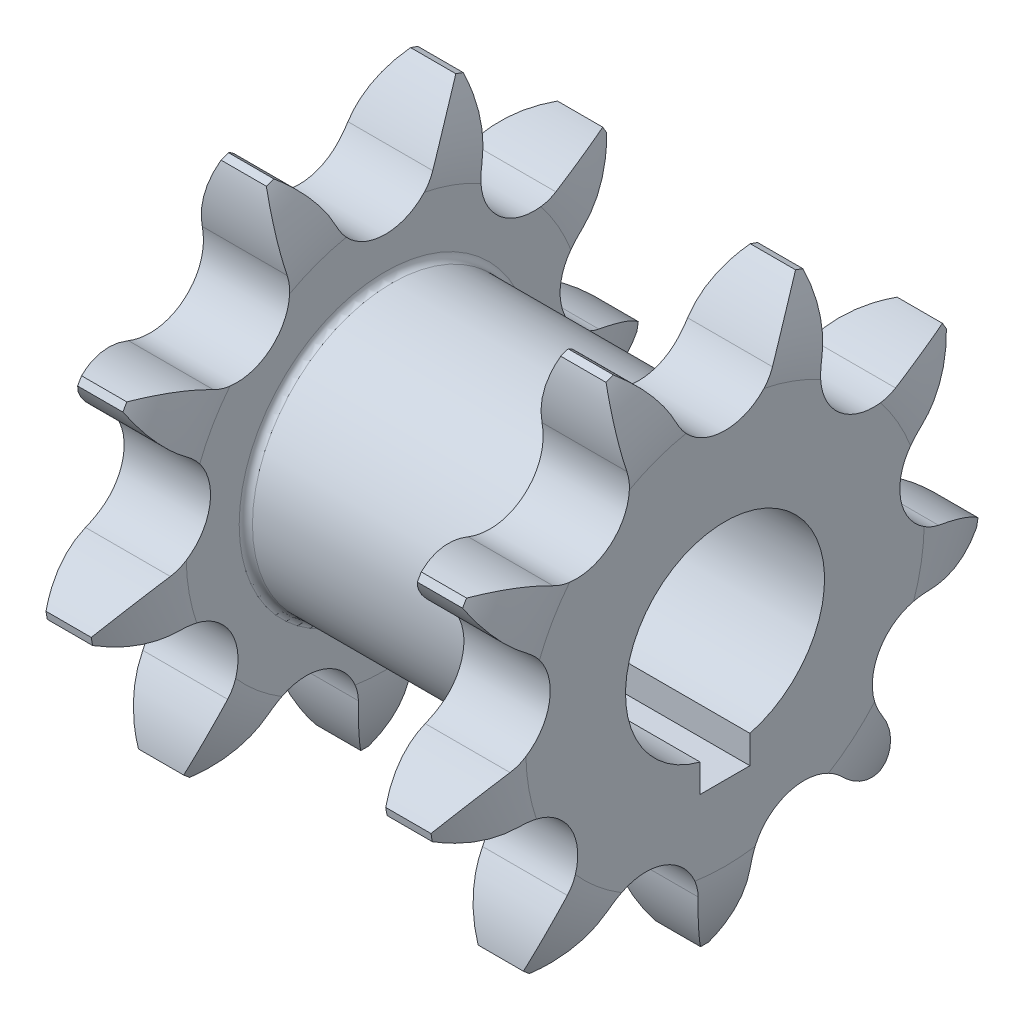
SolidWorks part; units mm, degrees
material "1.0503 (C45)"
ref_plane "Plane1" through (0, 0, 0) normal (0, 0, 1) x (1, 0, 0)
ref_plane "Plane2" through (0, 0, 0) normal (0, 1, 0) x (1, 0, 0)
ref_plane "Plane3" through (0, 0, 0) normal (1, 0, 0) x (0, 0, -1)
sketch "Clipboard" plane through (0, 0, 0) normal (0, 1, 0) x (1, 0, 0)
  line L0 (0, 0) -> (9.4077, -1.49)
  line L1 (-15, 0) -> (100, 0) construction
  line L2 (0, 0) -> (-0.8203, 0.9272)
  line L3 (0, 0) -> (-8.8973, 3.4006)
  line L4 (0, 0) -> (3.0618, 0.4849)
  line L5 (0, 0) -> (-46.8476, -17.4728)
  line L6 (0, 0) -> (-21.2921, -14.3658)
  line L7 (-0.8203, 0.9272) -> (48.0875, 11.3229)
  line L8 (-76.2, 38.1) -> (-73.9, 38.1)
  line L9 (-73.319, 40.6764) -> (-72.9207, 40.7126)
  line L10 (-73.4529, 9.1872) -> (-63.2129, 9.1872)
  circle A0 centre (0, 0) radius 3.175
  circle A1 centre (0, 0) radius 8.3684
  circle A2 centre (0, 0) radius 37.5
  dimension "Dr" = 6.35
  dimension "MHD" = 16.7367
  dimension "Hub_dia" = 75
  dimension "Num_teeth" = 9
  dimension "Pitch" = 9.525
  dimension "Width" = 3.1
  dimension "Side_relief" = 1.238
  dimension "Side_radius" = 9.525
  dimension "Overall_len" = 50
  dimension "Show_teeth" = 9
  dimension "Thickness" = 25.6852
  dimension "OAL" = 50.0005
  dimension "T_dim" = 2.3
  dimension "Fillet_rad" = 0.4
  dimension "Face_width" = 5.205
  dimension "Num_strands" = 3
  dimension "Transv_pitch" = 10.24
  dimension "Plate_wid" = 8.26
sketch "BasProSke" plane through (0, 0, 0) normal (0, 1, 0) x (1, 0, 0)
  line L0 (-10, 0) -> (60, 0) construction
  line L1 (0, 0) -> (0, 12.0069)
  line L2 (0, 0) -> (25.6852, 0)
  line L3 (25.6852, 0) -> (25.6852, 12.0069)
  line L4 (24.4472, 16.7027) -> (1.238, 16.7027)
  arc A0 (0, 12.0069) -> (1.238, 16.7027) centre (9.525, 12.0069) cw
  arc A1 (25.6852, 12.0069) -> (24.4472, 16.7027) centre (16.1602, 12.0069) ccw
  dimension "D1" = 9.525
  dimension "G1" = 1.238
  dimension "G2" = 1.238
  dimension "Diameter" = 33.4055
  dimension "Thickness" = 25.6852
revolve "Base-Revolve" add sketch "BasProSke" angle 360 about L0
sketch "GrvSke" plane through (0, 0, 0) normal (0, 1, 0) x (1, 0, 0)
  line L0 (5.2052, 12.0069) -> (5.2052, 8.8097)
  line L1 (5.6052, 8.4097) -> (9.84, 8.4097)
  line L2 (10.24, 8.8097) -> (10.24, 12.0069)
  line L3 (3.9672, 16.7027) -> (11.478, 16.7027)
  line L4 (7.7226, 0) -> (7.7226, 52.07) construction
  line L5 (-10, 0) -> (60, 0) construction
  line L6 (0, 0) -> (35.56, 0) construction
  arc A0 (10.24, 12.0069) -> (11.478, 16.7027) centre (19.765, 12.0069) cw
  arc A1 (5.2052, 12.0069) -> (3.9672, 16.7027) centre (-4.3198, 12.0069) ccw
  arc A2 (5.2052, 8.8097) -> (5.6052, 8.4097) centre (5.6052, 8.8097) ccw
  arc A3 (9.84, 8.4097) -> (10.24, 8.8097) centre (9.84, 8.8097) ccw
  dimension "D1" = 9.525
  dimension "Fillet_rad" = 0.4
  dimension "Diameter" = 33.4055
  dimension "Grv_diam" = 16.8193
  dimension "Grv_width" = 5.0348
  dimension "Offset" = 7.7226
  dimension "G1" = 1.238
revolve "Groove" cut sketch "GrvSke" angle 360 about L6
pattern_linear "Grooves" count 2 spacing 10.24 along (1, 0, 0) of "Groove"
sketch "TooCutSke" plane through (0, 0, 0) normal (1, 0, 0) x (0, 0, -1)
  line L0 (0, 13.9564) -> (2.9063, 12.6011) construction
  line L1 (0, 0) -> (0, 107) construction
  line L2 (0, 13.9564) -> (-10, 13.9564) construction
  line L3 (0, 13.9564) -> (-2.9063, 12.6011) construction
  arc A0 (2.9063, 12.6011) -> (5.9941, 16.1247) centre (10.503, 9.0588) cw
  arc A1 (2.9063, 12.6011) -> (-2.9063, 12.6011) centre (0, 13.9564) cw
  arc A2 (-2.9063, 12.6011) -> (-5.9941, 16.1247) centre (-10.503, 9.0588) ccw
  arc A3 (5.9941, 16.1247) -> (-5.9941, 16.1247) centre (0, 0) ccw
  dimension "R1" = 3.2067
  dimension "R2" = 8.382
  dimension "Overcut" = 17.2027
  dimension "Seat_radius" = 13.9564
  dimension "X" = 130
extrude "ToothCut" cut sketch "TooCutSke" along normal through all
pattern_circular "TeethCuts" count 9 every 40 about axis through (-10, 0, 0) along (1, 0, 0) of "ToothCut"
sketch "HubNeaOneSke" plane through (0, 0, 0) normal (-1, 0, 0) x (0, 0, 1)
  circle A0 centre (0, 0) radius 8.3684
  dimension "Diameter" = 16.7367
extrude "HubNearOne" [suppressed] add sketch "HubNeaOneSke" along normal blind 24.3153
fillet "HubNearOneFillet" [suppressed] radius 0.4
sketch "HubNeaBotSke" plane through (0, 0, 0) normal (-1, 0, 0) x (0, 0, 1)
  circle A0 centre (0, 0) radius 8.3684
  dimension "Diameter" = 16.7367
extrude "HubNearBoth" [suppressed] add sketch "HubNeaBotSke" along normal blind 12.1577
fillet "HubNearBothFillet" [suppressed] radius 0.4
ref_plane "FarPln" through (25.6852, 0, 0) normal (1, 0, 0) x (0, 0, -1)
sketch "HubFarSke" plane through (25.6852, 0, 0) normal (1, 0, 0) x (0, 0, -1)
  circle A0 centre (0, 0) radius 8.3684
  dimension "Diameter" = 16.7367
extrude "HubFar" [suppressed] add sketch "HubFarSke" along normal blind 12.1577
fillet "HubFarFillet" [suppressed] radius 0.4
sketch "BorSke" plane through (0, 0, 0) normal (1, 0, 0) x (0, 0, -1)
  circle A0 centre (0, 0) radius 6
  dimension "Diameter" = 12
extrude "Bore" cut sketch "BorSke" along normal mid plane 100.001
sketch "KeySke" plane through (0, 0, 0) normal (1, 0, 0) x (0, 0, -1)
  line L0 (-1.5, 0) -> (-1.5, -7.5)
  line L1 (-1.5, -7.5) -> (1.5, -7.5)
  line L2 (1.5, -7.5) -> (1.5, 0)
  line L3 (0, 0) -> (0, 34) construction
  line L4 (-1.5, 0) -> (1.5, 0)
  line L5 (0, -7.5) -> (0, -6) construction
  circle A0 centre (0, 0) radius 6 construction
  dimension "D1" = 1.5
  dimension "D2" = 3
extrude "Keyway" cut sketch "KeySke" along normal mid plane 100.001
pattern_circular "Keyway2" [suppressed] count 2 every 90 about axis through (-10, 0, 0) along (1, 0, 0)
sketch "Sketch1" plane through (20.48, 0, 0) normal (-1, 0, 0) x (0, 0, 1)
  circle A0 centre (0, 0) radius 8.4097 construction
  circle A1 centre (0, 0) radius 8.4097
extrude "Cut-Extrude1" cut sketch "Sketch1" along normal blind 10 from offset 3 flip side to cut
equation "' \"Pitch@Clipboard\" = 12.7"
equation "' \"Num_strands@Clipboard\" = 3"
equation "' \"Num_teeth@Clipboard\" = 9"
equation "' \"Hub_dia@Clipboard\" = 50"
equation "' \"Overall_len@Clipboard\" = 3"
equation "' \"Diameter@BorSke\" = 12"
equation "' \"T_dim@Clipboard\" = 1"
equation "' \"Width@KeySke\" = 2"
equation "' \"Dr@Clipboard\" = 8.51"
equation "' \"Face_width@Clipboard\" = 7.2"
equation "' \"Side_radius@Clipboard\" = 12.7"
equation "' \"Side_relief@Clipboard\" = 1.27"
equation "' \"Transv_pitch@Clipboard\" = 13.92"
equation "' \"Show_teeth@Clipboard\" = 9"
equation "' \"Fillet_rad@Clipboard\" = 0.6"
equation "' \"Plate_wid@Clipboard\" = 11.8"
